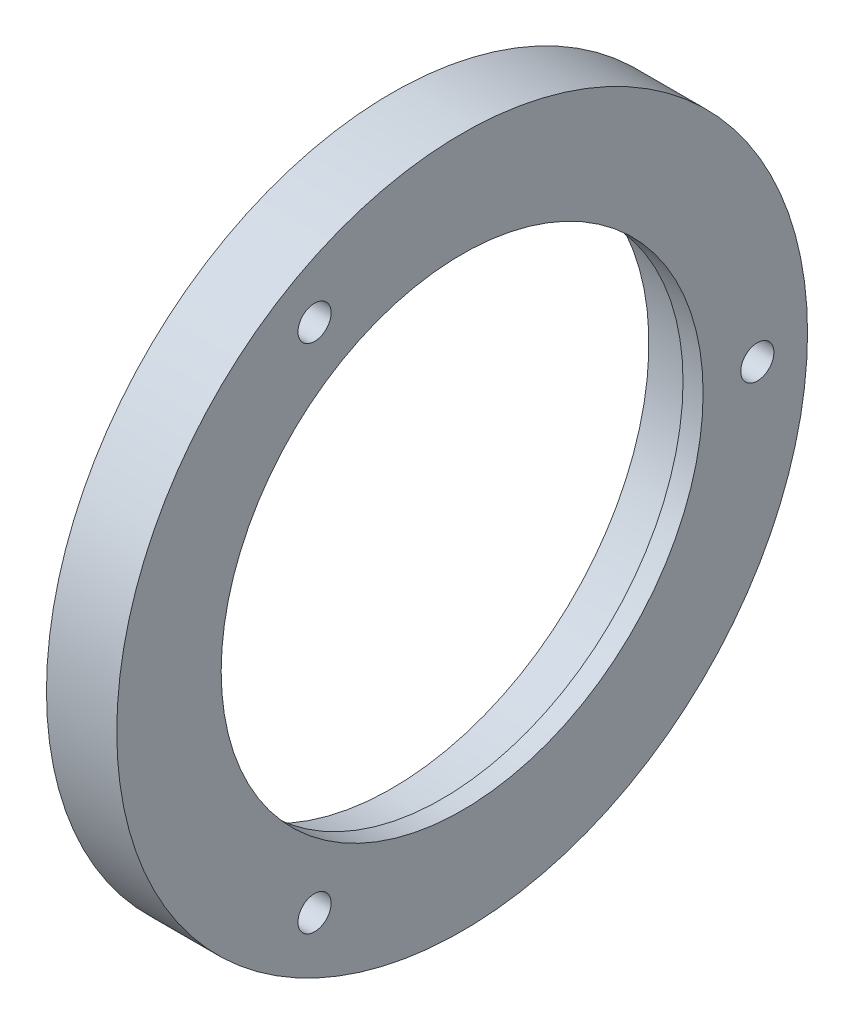
SolidWorks part; units mm, degrees
ref_plane "Front Plane" through (0, 0, 0) normal (0, 0, 1) x (1, 0, 0)
ref_plane "Top Plane" through (0, 0, 0) normal (0, 1, 0) x (1, 0, 0)
ref_plane "Right Plane" through (0, 0, 0) normal (1, 0, 0) x (0, 0, -1)
sketch "Axial profile (mm)" plane through (0, 0, 0) normal (0, 0, 1) x (1, 0, 0)
  line L0 (-110, 0) -> (75, 0) construction
  line L1 (169.7, 25.6) -> (174.7, 25.6)
  line L2 (174.7, 25.6) -> (174.7, 24)
  line L3 (174.7, 24) -> (176.7, 24)
  line L4 (176.7, 24) -> (176.7, 34.4)
  line L5 (176.7, 34.4) -> (169.7, 34.4)
  line L6 (169.7, 34.4) -> (169.7, 25.6)
revolve "Full revolution" add sketch "Axial profile (mm)" angle 360 about L0
sketch "Sketch2" plane through (0, 0, 0) normal (1, 0, 0) x (0, 0, -1)
  circle A0 centre (29.4, 0) radius 1.65
  circle A1 centre (-14.7, 25.4611) radius 1.65
  circle A2 centre (-14.7, -25.4611) radius 1.65
extrude "Axial holes" cut sketch "Sketch2" against normal through all and the other way through all
sketch "Sketch3" plane through (0, 0, 0) normal (1, 0, 0) x (0, 0, -1)
  circle A0 centre (29.4, 0) radius 3
  circle A1 centre (-14.7, 25.4611) radius 3
  circle A2 centre (-14.7, -25.4611) radius 3
extrude "Cut-Extrude2" cut sketch "Sketch3" against normal blind 2.7 from offset 174
